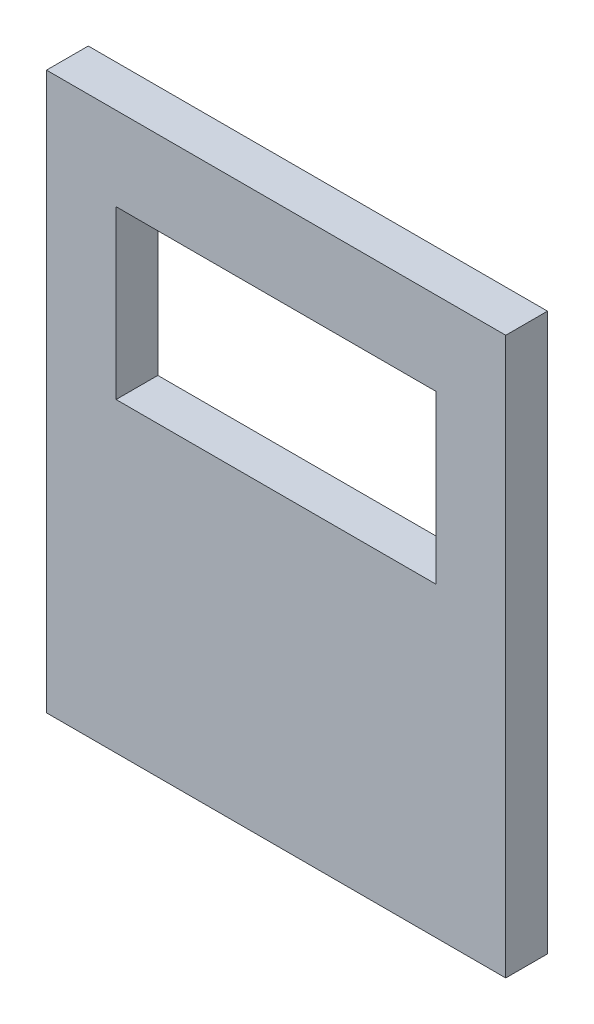
SolidWorks part; units mm, degrees
ref_plane "Plan de face" through (0, 0, 0) normal (0, 0, 1) x (1, 0, 0)
ref_plane "Plan de dessus" through (0, 0, 0) normal (0, 1, 0) x (1, 0, 0)
ref_plane "Plan de droite" through (0, 0, 0) normal (1, 0, 0) x (0, 0, -1)
sketch "Sketch1" plane through (0, 0, 0) normal (0, 0, 1) x (1, 0, 0)
  line L1 (-16.5, -20) -> (16.5, -20)
  line L2 (-16.5, -20) -> (-16.5, 20)
  line L3 (-16.5, 20) -> (16.5, 20)
  line L4 (16.5, -20) -> (16.5, 20)
  line L5 (-16.5, -20) -> (16.5, 20) construction
  line L6 (-16.5, 20) -> (16.5, -20) construction
  line L7 (-11.5, 14) -> (11.5, 14)
  line L8 (-11.5, 14) -> (-11.5, 2)
  line L9 (-11.5, 2) -> (11.5, 2)
  line L10 (11.5, 14) -> (11.5, 2)
  point P0 (0, 0)
  dimension "D1" = 33
  dimension "D2" = 40
  dimension "D3" = 23
  dimension "D4" = 12
  dimension "D5" = 6
  dimension "D6" = 5
extrude "Boss-Extrude1" add sketch "Sketch1" along normal blind 3
